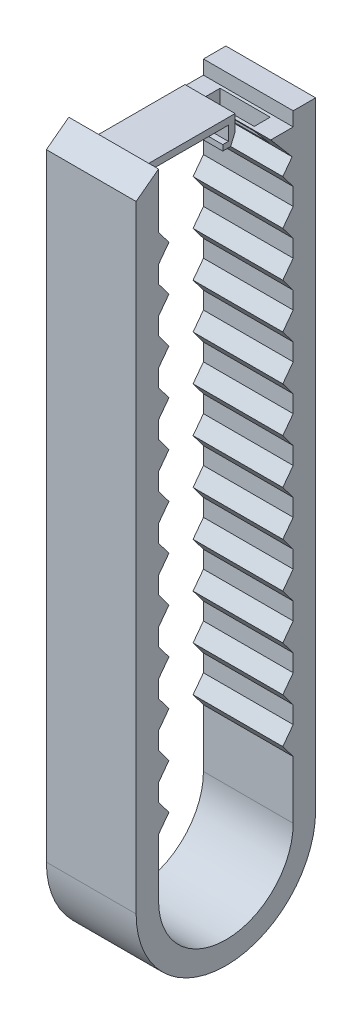
SolidWorks part; units mm, degrees
ref_plane "Front Plane" through (0, 0, 0) normal (1, 0, 0) x (0, 1, 0)
ref_plane "Top Plane" through (0, 0, 0) normal (0, 0, 1) x (0, 1, 0)
ref_plane "Right Plane" through (0, 0, 0) normal (0, 1, 0) x (-1, 0, 0)
sketch "Sketch2" plane through (0, 0, 0) normal (1, 0, 0) x (0, 1, 0)
  line L0 (55, 6) -> (0, 6)
  line L1 (0, -6) -> (55, -6)
  line L2 (0, -8.8) -> (0, 8.8) construction
  line L3 (55, 8) -> (0, 8)
  line L4 (0, -8) -> (55, -8)
  line L5 (55, 6) -> (55, 8)
  line L6 (55, -6) -> (55, -8)
  arc A0 (0, 6) -> (0, -6) centre (0, 0) ccw
  arc A1 (0, 8) -> (0, -8) centre (0, 0) ccw
  dimension "D1" = 2
extrude "Boss-Extrude1" add sketch "Sketch2" along normal blind 8
sketch "Sketch8" plane through (0, 0, 0) normal (1, 0, 0) x (0, 1, 0)
  line L0 (8.8837, 6.2) -> (11.8853, 6.2)
  line L1 (4.8837, 6.2) -> (7.8853, 6.2)
  line L5 (4.8837, 6.2) -> (6.3845, 5.075)
  line L6 (7.8853, 6.2) -> (6.3845, 5.075)
  line L7 (8.8837, 6.2) -> (10.3845, 5.075)
  line L8 (11.8853, 6.2) -> (10.3845, 5.075)
  line L9 (12.8837, 6.2) -> (15.8853, 6.2)
  line L10 (12.8837, 6.2) -> (14.3845, 5.075)
  line L11 (15.8853, 6.2) -> (14.3845, 5.075)
  line L12 (16.8837, 6.2) -> (19.8853, 6.2)
  line L13 (16.8837, 6.2) -> (18.3845, 5.075)
  line L14 (19.8853, 6.2) -> (18.3845, 5.075)
  line L15 (20.8837, 6.2) -> (23.8853, 6.2)
  line L16 (20.8837, 6.2) -> (22.3845, 5.075)
  line L17 (23.8853, 6.2) -> (22.3845, 5.075)
  line L18 (24.8837, 6.2) -> (27.8853, 6.2)
  line L19 (24.8837, 6.2) -> (26.3845, 5.075)
  line L20 (27.8853, 6.2) -> (26.3845, 5.075)
  line L21 (28.8837, 6.2) -> (31.8853, 6.2)
  line L22 (28.8837, 6.2) -> (30.3845, 5.075)
  line L23 (31.8853, 6.2) -> (30.3845, 5.075)
  line L24 (32.8837, 6.2) -> (35.8853, 6.2)
  line L25 (32.8837, 6.2) -> (34.3845, 5.075)
  line L26 (35.8853, 6.2) -> (34.3845, 5.075)
  line L27 (36.8837, 6.2) -> (39.8853, 6.2)
  line L28 (36.8837, 6.2) -> (38.3845, 5.075)
  line L29 (39.8853, 6.2) -> (38.3845, 5.075)
  line L30 (40.8837, 6.2) -> (43.8853, 6.2)
  line L31 (40.8837, 6.2) -> (42.3845, 5.075)
  line L32 (43.8853, 6.2) -> (42.3845, 5.075)
  line L33 (44.8837, 6.2) -> (47.8853, 6.2)
  line L34 (44.8837, 6.2) -> (46.3845, 5.075)
  line L35 (47.8853, 6.2) -> (46.3845, 5.075)
  line L36 (48.8837, 6.2) -> (51.8853, 6.2)
  line L37 (48.8837, 6.2) -> (50.3845, 5.075)
  line L38 (51.8853, 6.2) -> (50.3845, 5.075)
  dimension "D1" = 12
extrude "Boss-Extrude2" add sketch "Sketch8" along normal blind 8
mirror "Mirror1" about plane through (0, 0, 0) normal (0, 0, 1) of "Boss-Extrude2"
sketch "Sketch9" plane through (0, 0, 0) normal (1, 0, 0) x (0, 1, 0)
  line L0 (55, 6) -> (55, -2)
  line L1 (55, -2) -> (53.75, -2)
  line L2 (55.6, 6) -> (55.6, -2.6)
  line L3 (55.6, -2.6) -> (53.25, -2.6)
  line L5 (53.25, -2) -> (53.25, -2.6)
  line L6 (55.6, 6) -> (56.5035, 6)
  line L7 (56.5035, 6) -> (55, 8)
  line L8 (55, 8) -> (55, 6)
  line L9 (53.75, -2) -> (53.75, -1.5)
  line L18 (53.75, -1.5) -> (53.25, -1.5)
  line L19 (53.25, -1.5) -> (53.25, -2)
  line L20 (55, -2) -> (53.25, -2) construction
  line L21 (53.75, -4.0004) -> (51.3841, -6)
  line L23 (0, -6) -> (55, -6) construction
  line L24 (51.3841, -6) -> (53.75, -6)
  line L25 (53.75, -6) -> (53.75, -4.0004)
  dimension "D1" = 8
  dimension "D2" = 1.75
  dimension "D9" = 0.5
  dimension "D10" = 0.5
  dimension "D3" = 0.6
extrude "Boss-Extrude4" add sketch "Sketch9" along normal blind 8
sketch "Sketch10" plane through (0, 53.75, 0) normal (0, 1, 0) x (-1, 0, 0)
  line L0 (-6.2215, -4.3023) -> (-6.2215, -5.7312)
  line L1 (-6.2215, -5.7312) -> (-1.7525, -5.7312)
  line L2 (-1.7525, -5.7312) -> (-1.7525, -4.3023)
  line L3 (-1.7525, -4.3023) -> (-6.2215, -4.3023)
extrude "Cut-Extrude2" cut sketch "Sketch10" against normal blind 2
sketch "Sketch11" plane through (0, 55.6, 0) normal (0, 1, 0) x (-1, 0, 0)
  line L0 (-6.2215, -2.6) -> (-6.2215, 6)
  line L1 (-8, -2.6) -> (0, -2.6) construction
  line L2 (-8, 6) -> (0, 6) construction
  line L3 (-6.2215, 6) -> (-8, 6)
  line L4 (-8, 6) -> (-8, -2.6)
  line L5 (-8, -2.6) -> (-6.2215, -2.6)
  line L6 (-1.7525, -2.6) -> (-1.7525, 6)
  line L7 (-1.7525, 6) -> (0, 6)
  line L8 (0, 8) -> (0, -8) construction
  line L9 (0, 6) -> (0, -6) construction
  line L10 (0, 6) -> (0, -2.6)
  line L11 (0, -2.6) -> (-1.7525, -2.6)
extrude "Cut-Extrude4" cut sketch "Sketch11" against normal blind 2.5
sketch "Sketch12" plane through (1.7525, 0, 0) normal (-1, 0, 0) x (0, -1, 0)
  line L2 (-53.25, -2.6) -> (-53.25, -2.1997)
  line L4 (-53.75, -2.6) -> (-53.25, -2.6)
  line L5 (-53.25, -2.6) -> (-55.6, -2.6) construction
  line L7 (-53.25, -1.5) -> (-53.25, -2.6) construction
  line L8 (-53.25, -2.1997) -> (-54.173, -2.6)
  line L10 (-54.173, -2.6) -> (-53.75, -2.6)
extrude "Cut-Extrude6" cut sketch "Sketch12" against normal blind 14.47
